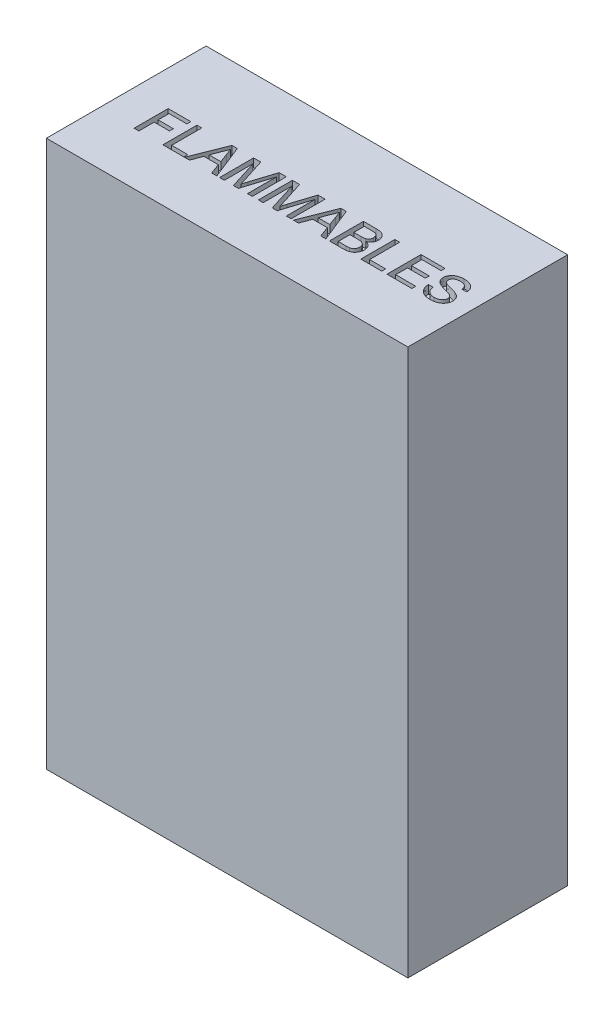
SolidWorks part; units mm, degrees
ref_plane "Front" through (0, 0, 0) normal (0, 0, 1) x (1, 0, 0)
ref_plane "Top" through (0, 0, 0) normal (0, 1, 0) x (1, 0, 0)
ref_plane "Right" through (0, 0, 0) normal (1, 0, 0) x (0, 0, -1)
sketch "Sketch1" plane through (0, 0, 0) normal (0, 1, 0) x (1, 0, 0)
  line L1 (-546.1, 241.3) -> (546.1, 241.3)
  line L2 (-546.1, 241.3) -> (-546.1, -241.3)
  line L3 (-546.1, -241.3) -> (546.1, -241.3)
  line L4 (546.1, 241.3) -> (546.1, -241.3)
  line L5 (-546.1, 241.3) -> (546.1, -241.3) construction
  line L6 (-546.1, -241.3) -> (546.1, 241.3) construction
  point P0 (0, 0)
  dimension "D1" = 1092.2
  dimension "D2" = 482.6
extrude "Boss-Extrude1" add sketch "Sketch1" along normal blind 1651
sketch "Sketch2" plane through (0, 1651, 0) normal (0, 1, 0) x (1, 0, 0)
  line L0 (-451.6231, -82.4589) -> (464.5155, -82.4589) construction
  text T0 "FLAMMABLES" font "Arial" height in points 400
extrude "Cut-Extrude1" cut sketch "Sketch2" against normal blind 25.4
